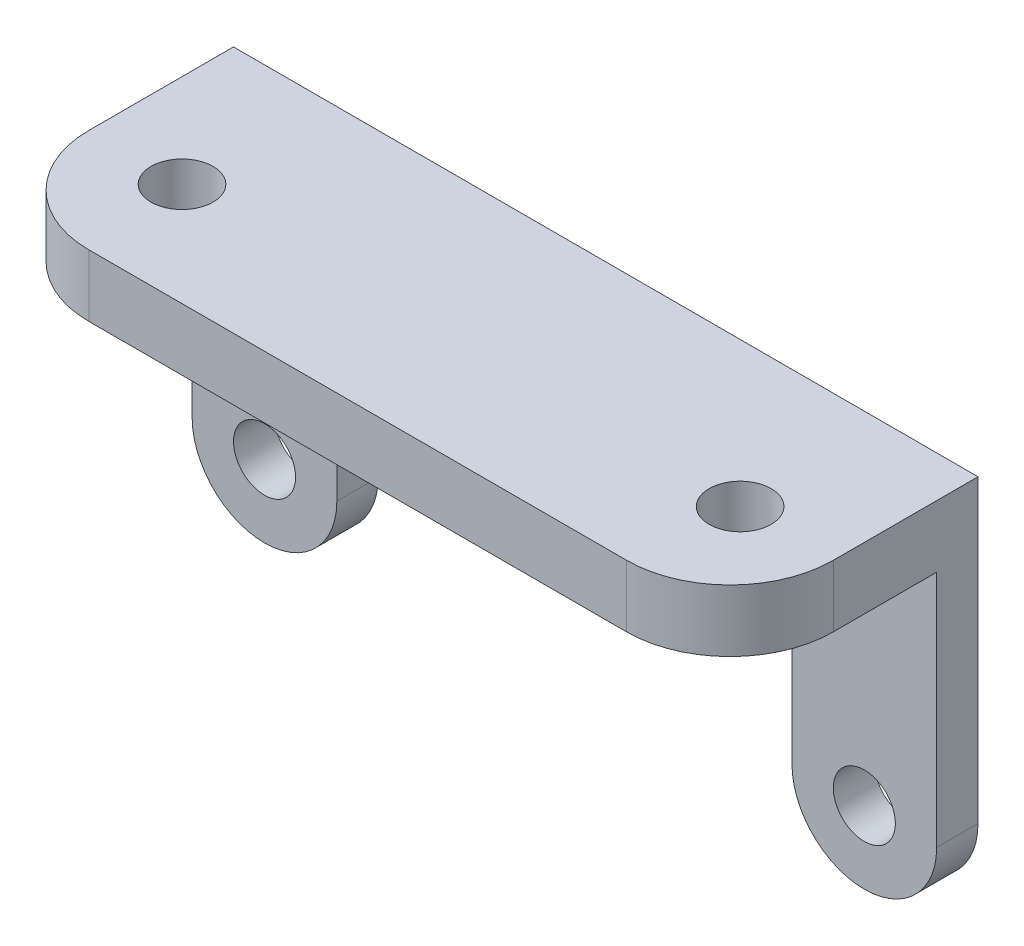
SolidWorks part; units mm, degrees
ref_plane "前视基准面" through (0, 0, 0) normal (0, 0, 1) x (1, 0, 0)
ref_plane "上视基准面" through (0, 0, 0) normal (0, 1, 0) x (1, 0, 0)
ref_plane "右视基准面" through (0, 0, 0) normal (1, 0, 0) x (0, 0, -1)
other "Configuration Table"
sketch "草图1" plane through (0, 0, 0) normal (0, 0, 1) x (1, 0, 0)
  line L0 (0, 0) -> (0, -74.7558) construction
  line L1 (-18.0085, 2.5) -> (18.0085, 2.5)
  line L2 (-18.0085, 2.5) -> (-18.0085, -2.5)
  line L4 (18.0085, 2.5) -> (18.0085, -2.5)
  line L5 (-18.0085, 2.5) -> (18.0085, -2.5) construction
  line L6 (-18.0085, -2.5) -> (18.0085, 2.5) construction
  line L7 (-18.0085, -12.0321) -> (-18.0085, -2.5)
  line L9 (-11.0085, -3.5958) -> (-11.0085, -12.0321)
  line L10 (-11.0085, -3.5958) -> (11.0085, -3.5958)
  line L11 (11.0085, -3.5958) -> (11.0085, -12.0321)
  line L12 (18.0085, -12.0321) -> (18.0085, -2.5)
  circle A0 centre (-14.5085, -12.0321) radius 1.5
  arc A2 (-18.0085, -12.0321) -> (-11.0085, -12.0321) centre (-14.5085, -12.0321) ccw
  circle A3 centre (-14.5085, -12.0321) radius 3.5 construction
  circle A4 centre (14.5085, -12.0321) radius 1.5
  arc A5 (18.0085, -12.0321) -> (11.0085, -12.0321) centre (14.5085, -12.0321) cw
  point P0 (0, 0)
  point P13 (14.5085, -11.4325)
  point P14 (14.5085, -12.0321)
  dimension "D1" = 3
  dimension "D2" = 2
  dimension "D4" = 5
  dimension "D5" = 29.017
extrude "凸台-拉伸1" add sketch "草图1" along normal blind 2
sketch "草图2" plane through (0, 0, 2) normal (0, 0, 1) x (1, 0, 0)
  line L0 (18.0085, -12.0321) -> (18.0085, 2.5) construction
  line L1 (-18.0085, 2.5) -> (18.0085, 2.5)
  line L2 (-18.0085, 2.5) -> (-18.0085, -0.5)
  line L3 (-18.0085, -0.5) -> (18.0085, -0.5)
  line L4 (18.0085, 2.5) -> (18.0085, -0.5)
  dimension "D1" = 3
extrude "凸台-拉伸2" add sketch "草图2" along normal blind 10
sketch "草图3" plane through (0, 2.5, 0) normal (0, 1, 0) x (1, 0, 0)
  line L0 (18.0085, 0) -> (-18.0085, 0) construction
  line L1 (18.0085, 0) -> (-18.0085, 0) construction
  line L2 (0, 0) -> (0, -15.2444) construction
  line L4 (18.0085, -12) -> (-18.0085, -12) construction
  circle A0 centre (-13.5, -7) radius 1.5
  circle A1 centre (13.5, -7) radius 1.5
  dimension "D1" = 3
  dimension "D3" = 5
  dimension "D2" = 27
extrude "切除-拉伸1" cut sketch "草图3" against normal through all
fillet "圆角1" radius 5 2 edges at (18.0085, 1, 12) (-18.0085, 1, 12)
